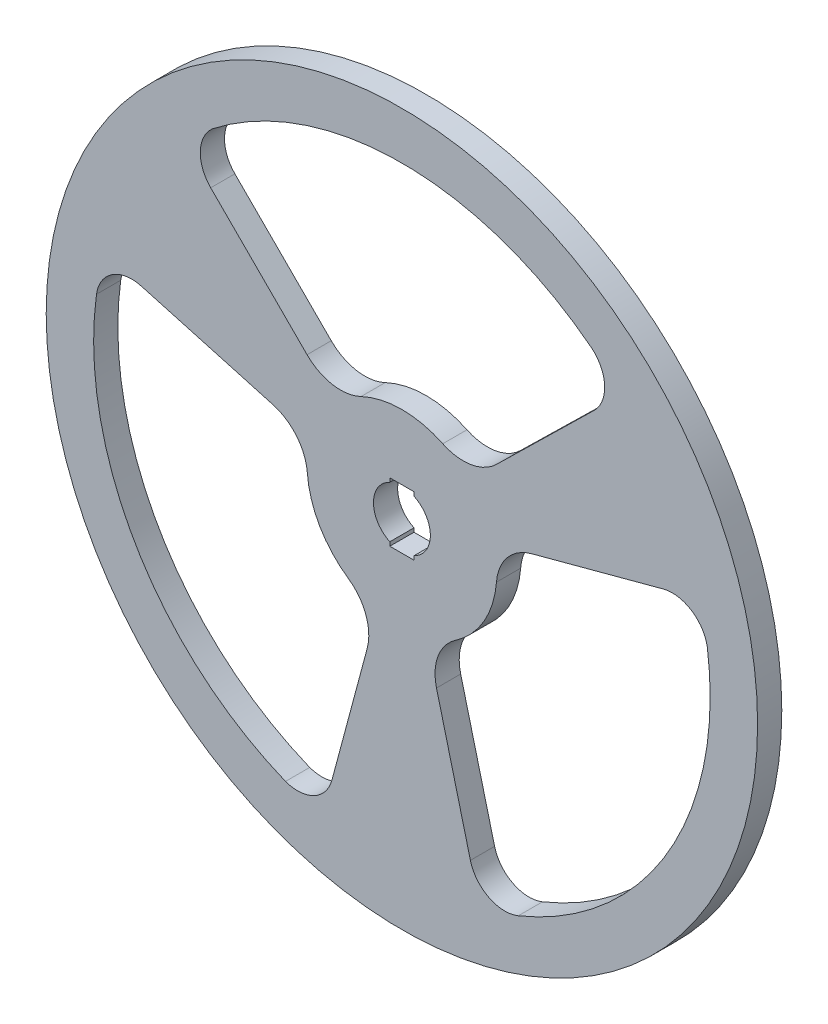
SolidWorks part; units mm, degrees
ref_plane "Front Plane" through (0, 0, 0) normal (0, 0, 1) x (1, 0, 0)
ref_plane "Top Plane" through (0, 0, 0) normal (0, 1, 0) x (1, 0, 0)
ref_plane "Right Plane" through (0, 0, 0) normal (1, 0, 0) x (0, 0, -1)
ref_plane "Plane1"
sketch "Sketch1" plane through (0, 0, 0) normal (0, 0, 1) x (1, 0, 0)
  line L0 (27.3205, 7.3205) -> (55.0735, 14.7569)
  line L1 (14.4429, -55.1072) -> (7.293, -27.2155)
  line L2 (-7.3205, -27.3205) -> (-14.7569, -55.0735)
  line L3 (-54.9457, 15.0457) -> (-27.2158, 7.2918)
  line L4 (-20, 20) -> (-40.3166, 40.3166)
  line L5 (40.5028, 40.0615) -> (19.9228, 19.9236)
  circle A0 centre (0, 0) radius 75
  circle A1 centre (0, 0) radius 6
  arc A2 (11.3198, -16.4882) -> (7.293, -27.2155) centre (16.9798, -24.7323) ccw
  arc A3 (11.3198, -16.4882) -> (19.9391, -1.5592) centre (0, 0) ccw
  arc A4 (27.3205, 7.3205) -> (19.9391, -1.5592) centre (29.9087, -2.3388) ccw
  arc A5 (64.3956, 8.8431) -> (55.0735, 14.7569) centre (57.0146, 7.5125) ccw
  arc A6 (24.5394, -60.1898) -> (64.3956, 8.8431) centre (0, 0) ccw
  arc A7 (14.4429, -55.1072) -> (24.5394, -60.1898) centre (21.708, -53.2449) ccw
  arc A8 (-19.9391, -1.5592) -> (-27.2158, 7.2918) centre (-29.9087, -2.3388) ccw
  arc A9 (-19.9391, -1.5592) -> (-11.3198, -16.4882) centre (0, 0) ccw
  arc A10 (-7.3205, -27.3205) -> (-11.3198, -16.4882) centre (-16.9798, -24.7323) ccw
  arc A11 (-24.5394, -60.1898) -> (-14.7569, -55.0735) centre (-22.0013, -53.1323) ccw
  arc A12 (-64.3956, 8.8431) -> (-24.5394, -60.1898) centre (0, 0) ccw
  arc A13 (-54.9457, 15.0457) -> (-64.3956, 8.8431) centre (-56.9654, 7.8228) ccw
  arc A14 (8.6193, 18.0474) -> (19.9228, 19.9236) centre (12.9289, 27.0711) ccw
  arc A15 (8.6193, 18.0474) -> (-8.6193, 18.0474) centre (0, 0) ccw
  arc A16 (-20, 20) -> (-8.6193, 18.0474) centre (-12.9289, 27.0711) ccw
  arc A17 (-39.8562, 51.3467) -> (-40.3166, 40.3166) centre (-35.0133, 45.6199) ccw
  arc A18 (39.8562, 51.3467) -> (-39.8562, 51.3467) centre (0, 0) ccw
  arc A19 (40.5028, 40.0615) -> (39.8562, 51.3467) centre (35.2574, 45.4221) ccw
  dimension "D1" = 150
  dimension "D2" = 40
  dimension "D3" = 15
  dimension "D4" = 15
  dimension "D5" = 20
  dimension "D6" = 20
  dimension "D7" = 65
  dimension "D11" = 12
  dimension "D8" = 29.378
  dimension "D9" = 28.2135
  dimension "D10" = 7.5
extrude "Extrusion1" add sketch "Sketch1" along normal blind 5.1 contours A0 A19 L5 A14 A15 A16 L4 A17 A18 A13 L3 A8 A9 A10 L2 A11 A12 A7 L1 A2 A3 A4 L0 A5 A6 A1
sketch "Sketch2" plane through (0, 0, 5.1) normal (0, 0, 1) x (1, 0, 0)
  line L1 (2.55, -6.25) -> (-2.55, -6.25)
  line L2 (2.55, -6.25) -> (2.55, 6.25)
  line L3 (2.55, 6.25) -> (-2.55, 6.25)
  line L4 (-2.55, -6.25) -> (-2.55, 6.25)
  line L5 (2.55, -6.25) -> (-2.55, 6.25) construction
  line L6 (2.55, 6.25) -> (-2.55, -6.25) construction
  point P0 (0, 0)
  circle M29 centre (0, 0) radius 6
  dimension "D1" = 5.1
  dimension "D2" = 12.5
extrude "Cut-Extrude1" cut sketch "Sketch2" against normal through all contours L4 L2 M29 | L4 L2 L3 M29 | L4 L1 L2 M29
